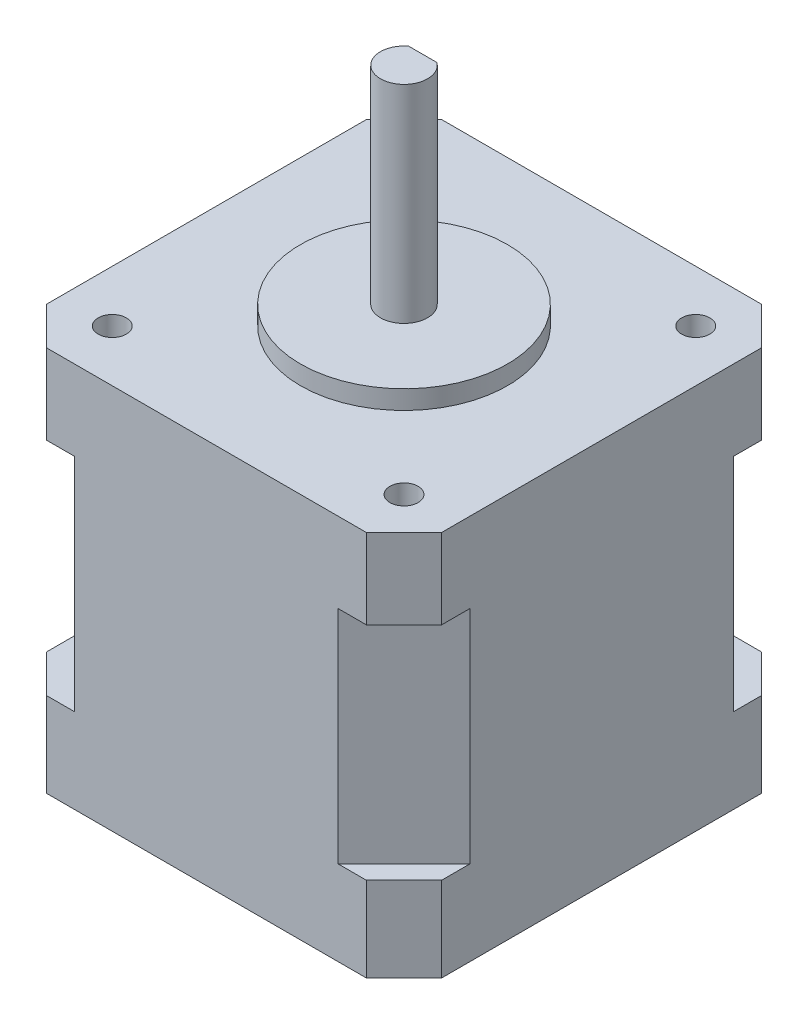
SolidWorks part; units mm, degrees
ref_plane "Plan de face" through (0, 0, 0) normal (0, 0, 1) x (1, 0, 0)
ref_plane "Plan de dessus" through (0, 0, 0) normal (0, 1, 0) x (1, 0, 0)
ref_plane "Plan de droite" through (0, 0, 0) normal (1, 0, 0) x (0, 0, -1)
sketch "Esquisse1" plane through (0, 0, 0) normal (0, 1, 0) x (1, 0, 0)
  line L1 (-21, 21) -> (21, 21)
  line L2 (-21, 21) -> (-21, -21)
  line L3 (-21, -21) -> (21, -21)
  line L4 (21, 21) -> (21, -21)
  point P4 (0, 21)
  point P6 (-21, 0)
  dimension "D1" = 42
extrude "Boss.-Extru.1" add sketch "Esquisse1" along normal blind 41
sketch "Esquisse2" plane through (0, 41, 0) normal (0, 1, 0) x (1, 0, 0)
  circle A0 centre (0, 0) radius 11
  dimension "D1" = 22
extrude "Boss.-Extru.2" add sketch "Esquisse2" along normal blind 2
sketch "Esquisse3" plane through (0, 43, 0) normal (0, 1, 0) x (1, 0, 0)
  line L0 (-1.5, 2) -> (1.5, 2)
  arc A1 (-1.5, 2) -> (1.5, 2) centre (0, 0) ccw
  point P6 (0, -2.5)
  dimension "D1" = 2.5
  dimension "D2" = 4.5
extrude "Boss.-Extru.3" add sketch "Esquisse3" along normal blind 22
hole_wizard "Diamètre du perçage Ø3.0 (3)1" positions "Esquisse7" profile "Esquisse6" hole size "Ø3.0" standard "DIN"
sketch "Esquisse7" plane through (0, 41, 0) normal (0, 1, 0) x (1, 0, 0)
  line L0 (0, 0) -> (0, 4.5387) construction
  line L2 (0, 0) -> (4.1956, 0) construction
  point P0 (-15.5, 15.5)
  point P12 (15.5, 15.5)
  point P13 (15.5, -15.5)
  point P14 (-15.5, -15.5)
  dimension "D1" = 31
  dimension "D2" = 31
sketch "Esquisse6" plane through (-15.5, 41, -15.5) normal (1, 0, 0) x (0, 0, 1)
  line L0 (0, 0) -> (0, 5.7013)
  line L1 (0, 5.7013) -> (1.5, 4.8)
  line L2 (1.5, 4.8) -> (1.5, 0)
  line L5 (1.5, 0) -> (0, 0)
  line L10 (0, 5.7013) -> (-1.5, 4.8) construction
  line L11 (0, -6.35) -> (0, 107.95) construction
  dimension "Diamètre du perçage" = 3
  dimension "Profondeur du perçage" = 4.8
  dimension "Angle de pointe" = 118
chamfer "Chanfrein1" distance 4 angle 45 4 edges at (-21, 20.5, -21) (21, 20.5, -21) (21, 20.5, 21) (-21, 20.5, 21)
sketch "Esquisse4" plane through (0, 0, 0) normal (0, 1, 0) x (1, 0, 0)
  line L0 (0, 0) -> (0, 5.1071) construction
  line L1 (0, 0) -> (5.8035, 0) construction
  line L2 (-14, 21) -> (-21, 14)
  line L3 (17, 21) -> (-17, 21) construction
  line L4 (-21, 17) -> (-21, -17) construction
  line L5 (-21, 14) -> (-21, 21)
  line L6 (-21, 21) -> (-14, 21)
  line L7 (21, 21) -> (14, 21)
  line L8 (21, 14) -> (21, 21)
  line L9 (14, 21) -> (21, 14)
  line L10 (14, -21) -> (21, -14)
  line L11 (21, -14) -> (21, -21)
  line L12 (21, -21) -> (14, -21)
  line L13 (-21, -21) -> (-14, -21)
  line L14 (-21, -14) -> (-21, -21)
  line L15 (-14, -21) -> (-21, -14)
  point P13 (0, 0)
  dimension "D1" = 7
extrude "Enlèv. mat.-Extru.1" cut sketch "Esquisse4" along normal blind 23.5 from offset 9
sketch "Esquisse5" plane through (-21, 0, 0) normal (-1, 0, 0) x (0, 0, 1)
  line L0 (0, 0) -> (0, 2.0466) construction
  line L1 (-17, 0) -> (17, 0) construction
  circle A0 centre (-1, 7) radius 0.7
  circle A1 centre (-1, 5) radius 0.6547
  circle A2 centre (1, 5) radius 0.6547
  circle A3 centre (1, 7) radius 0.7
  dimension "D2" = 1.4
  dimension "D1" = 2
  dimension "D3" = 2
  dimension "D4" = 5
extrude "Boss.-Extru.4" add sketch "Esquisse5" along normal blind 10
equation "\"D3@Esquisse5\"=\"D1@Esquisse5\""
equation "\"D2@Esquisse7\"=\"D1@Esquisse7\""
